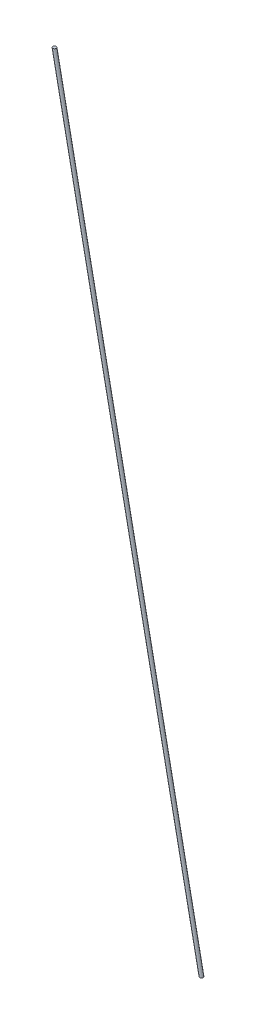
SolidWorks part; units mm, degrees
ref_plane "Front Plane" through (0, 0, 0) normal (0, 0, 1) x (1, 0, 0)
ref_plane "Top Plane" through (0, 0, 0) normal (0, 1, 0) x (1, 0, 0)
ref_plane "Right Plane" through (0, 0, 0) normal (1, 0, 0) x (0, 0, -1)
sketch "Sketch1" plane through (0, 0, 0) normal (0, 0, 1) x (1, 0, 0)
  line L0 (0, 0) -> (21.1285, -855) construction
  line L1 (21.1285, -855) -> (171.1285, -851.2932) construction
  line L2 (0, 0) -> (171.1285, -851.2932)
  dimension "D1" = 855
  dimension "D2" = 150
sketch "Sketch2" plane through (0, 0, 0) normal (0, 1, 0) x (1, 0, 0)
  circle A0 centre (0, 0) radius 2
  dimension "D1" = 4
sweep "Sweep1" add profiles "Sketch2" path "Sketch1"
